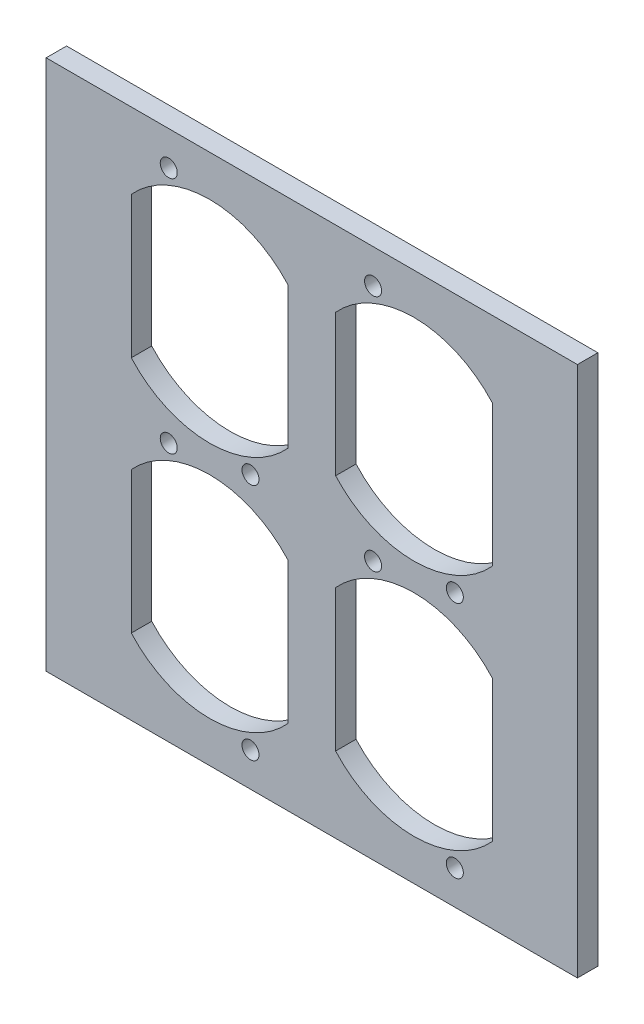
SolidWorks part; units mm, degrees
ref_plane "Front Plane" through (0, 0, 0) normal (0, 0, 1) x (1, 0, 0)
ref_plane "Top Plane" through (0, 0, 0) normal (0, 1, 0) x (1, 0, 0)
ref_plane "Right Plane" through (0, 0, 0) normal (1, 0, 0) x (0, 0, -1)
sketch "Sketch1" plane through (0, 0, 0) normal (0, 0, 1) x (1, 0, 0)
  line L1 (-39, -39) -> (39, -39)
  line L2 (-39, -39) -> (-39, 39)
  line L3 (-39, 39) -> (39, 39)
  line L4 (39, -39) -> (39, 39)
  line L5 (-39, -39) -> (39, 39) construction
  line L6 (-39, 39) -> (39, -39) construction
  point P0 (0, 0)
  dimension "D1" = 78
  dimension "D2" = 78
extrude "Boss-Extrude1" add sketch "Sketch1" along normal blind 3
sketch "Sketch2" plane through (0, 0, 0) normal (0, 0, -1) x (-1, 0, 0)
  line L0 (-26.5, 27.8923) -> (-26.5, 7.1077)
  line L1 (-3.5, 27.8923) -> (-3.5, 7.1077)
  line L2 (-26.5, 17.5) -> (-3.5, 17.5) construction
  arc A0 (-26.5, 7.1077) -> (-3.5, 7.1077) centre (-15, 17.5) ccw
  arc A1 (-26.5, 27.8923) -> (-3.5, 27.8923) centre (-15, 17.5) cw
  point P9 (-15, 33)
  point P10 (-15, 2)
  dimension "D1" = 31
  dimension "D2" = 23
  dimension "D3" = 17.5
  dimension "D4" = 15
extrude "Cut-Extrude1" cut sketch "Sketch2" against normal through all
sketch "Sketch3" plane through (0, 0, 0) normal (0, 0, -1) x (-1, 0, 0)
  line L0 (-26.5, 27.8923) -> (-26.5, 7.1077) construction
  circle A0 centre (-21, 1) radius 1.25
  circle A1 centre (-9, 34) radius 1.25
  arc A2 (-26.5, 7.1077) -> (-3.5, 7.1077) centre (-15, 17.5) ccw construction
  point P4 (-15, 2)
  point P8 (-26.5, 17.5)
  point P11 (-26.5, 17.5)
  dimension "D3" = 2.5
  dimension "D6" = 2.5
  dimension "D1" = 6
  dimension "D2" = 6
  dimension "D4" = 16.5
  dimension "D5" = 16.5
extrude "Cut-Extrude2" cut sketch "Sketch3" against normal through all
sketch "Sketch4" plane through (0, 0, 0) normal (0, 0, -1) x (-1, 0, 0)
  line L0 (-26.5, 27.8923) -> (-26.5, 7.1077) construction
  line L1 (-25.5, 28.9018) -> (-26.5, 28.9018)
  line L2 (-25.5, 28.9018) -> (-25.5, 6.0982)
  line L3 (-25.5, 6.0982) -> (-26.5, 6.0982)
  line L4 (-26.5, 28.9018) -> (-26.5, 6.0982)
  line L5 (-4.5, 28.9018) -> (-3.5, 28.9018)
  line L6 (-4.5, 28.9018) -> (-4.5, 6.0982)
  line L7 (-4.5, 6.0982) -> (-3.5, 6.0982)
  line L8 (-3.5, 28.9018) -> (-3.5, 6.0982)
  line L9 (-3.5, 7.1077) -> (-3.5, 27.8923) construction
  arc A0 (-3.5, 27.8923) -> (-26.5, 27.8923) centre (-15, 17.5) ccw construction
  arc A1 (-26.5, 7.1077) -> (-3.5, 7.1077) centre (-15, 17.5) ccw construction
  dimension "D1" = 1
  dimension "D2" = 1
extrude "Boss-Extrude2" [suppressed] add sketch "Sketch4" against normal blind 5
pattern_linear "LPattern1" count 2 spacing 30 along (-1, 0, 0) count 2 spacing 35 along (0, -1, 0) of "Cut-Extrude1", "Cut-Extrude2"
